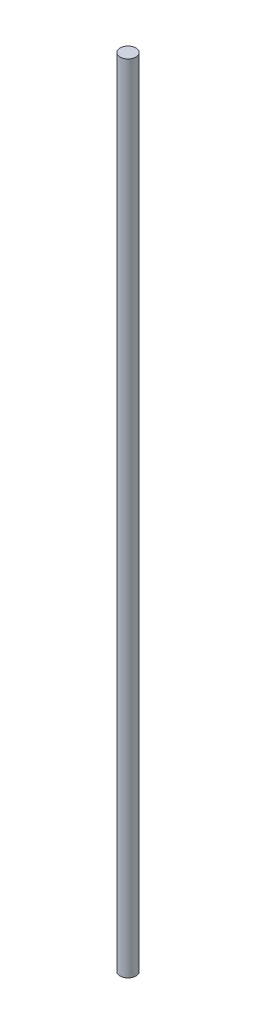
SolidWorks part; units mm, degrees
material "AISI 316 Annealed Stainless Steel Bar (SS)"
ref_plane "Front Plane" through (0, 0, 0) normal (0, 0, 1) x (1, 0, 0)
ref_plane "Top Plane" through (0, 0, 0) normal (0, 1, 0) x (1, 0, 0)
ref_plane "Right Plane" through (0, 0, 0) normal (1, 0, 0) x (0, 0, -1)
sketch "Sketch1" plane through (0, 0, 0) normal (0, 1, 0) x (1, 0, 0)
  circle A0 centre (0, 0) radius 4
  dimension "D1" = 8
extrude "Boss-Extrude1" add sketch "Sketch1" along normal mid plane 400
